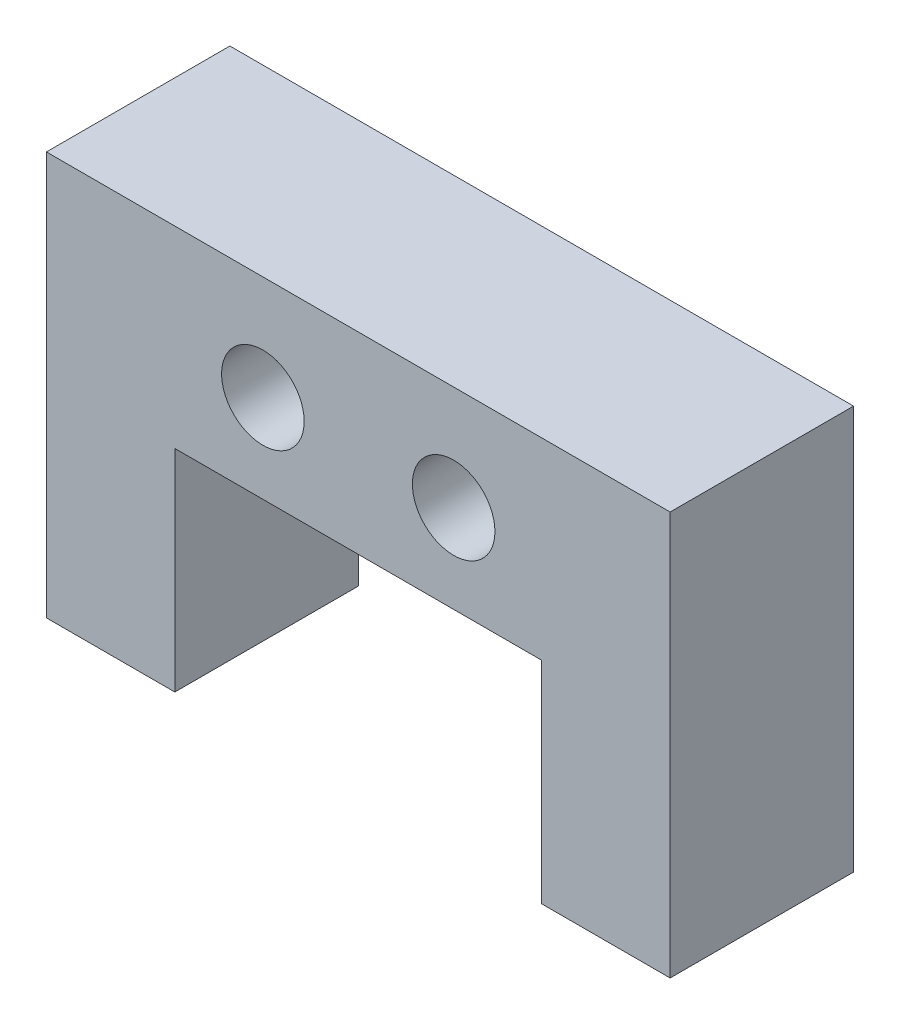
SolidWorks part; units mm, degrees
ref_plane "Front Plane" through (0, 0, 0) normal (0, 0, 1) x (1, 0, 0)
ref_plane "Top Plane" through (0, 0, 0) normal (0, 1, 0) x (1, 0, 0)
ref_plane "Right Plane" through (0, 0, 0) normal (1, 0, 0) x (0, 0, -1)
sketch "Sketch1" plane through (0, 0, 0) normal (0, 0, 1) x (1, 0, 0)
  line L0 (27, 0) -> (34, 0)
  line L1 (0, 0) -> (7, 0)
  line L2 (0, 0) -> (0, 22)
  line L3 (0, 22) -> (34, 22)
  line L4 (34, 0) -> (34, 22)
  line L6 (7, 0) -> (7, 11.5)
  line L7 (7, 11.5) -> (27, 11.5)
  line L8 (27, 0) -> (27, 11.5)
  circle A0 centre (22.2, 16.3) radius 2.25
  circle A1 centre (11.8, 16.3) radius 2.25
  dimension "D6" = 4.5
  dimension "D1" = 22
  dimension "D2" = 34
  dimension "D3" = 7
  dimension "D4" = 20
  dimension "D5" = 11.5
  dimension "D7" = 4.8
  dimension "D8" = 4.8
  dimension "D9" = 10.4
extrude "Boss-Extrude1" add sketch "Sketch1" along normal blind 10
